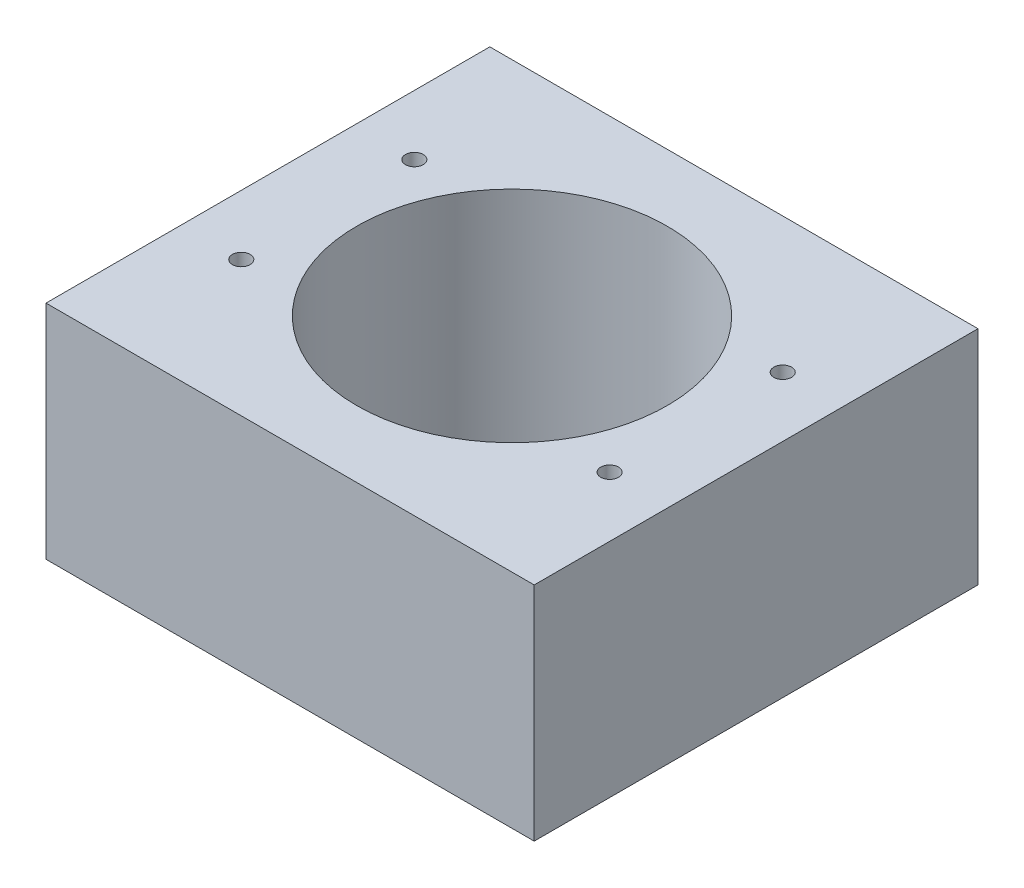
SolidWorks part; units mm, degrees
ref_plane "Front Plane" through (0, 0, 0) normal (0, 0, 1) x (1, 0, 0)
ref_plane "Top Plane" through (0, 0, 0) normal (0, 1, 0) x (1, 0, 0)
ref_plane "Right Plane" through (0, 0, 0) normal (1, 0, 0) x (0, 0, -1)
sketch "Sketch1" plane through (0, 0, 0) normal (0, 1, 0) x (1, 0, 0)
  line L1 (-55, 50) -> (55, 50)
  line L2 (-55, 50) -> (-55, -50)
  line L3 (-55, -50) -> (55, -50)
  line L4 (55, 50) -> (55, -50)
  line L5 (-55, 50) -> (55, -50) construction
  line L6 (-55, -50) -> (55, 50) construction
  point P0 (0, 0)
extrude "Boss-Extrude1" add sketch "Sketch1" along normal blind 50
sketch "Sketch2" plane through (0, 0, 0) normal (0, 1, 0) x (1, 0, 0)
  circle A0 centre (0, 0) radius 35
extrude "Cut-Extrude1" cut sketch "Sketch2" along normal blind 50
sketch "Sketch3" plane through (0, 0, 0) normal (0, 1, 0) x (1, 0, 0)
  line L0 (-55, -50) -> (55, -50) construction
  line L1 (55, -50) -> (55, 50) construction
  circle A0 centre (41.5, -19.5) radius 2
  dimension "D1" = 4
  dimension "D2" = 13.5
  dimension "29.5" = 30.5
extrude "Cut-Extrude2" cut sketch "Sketch3" along normal blind 50
mirror "Mirror1" about plane through (0, 0, 0) normal (0, 0, 1) of "Cut-Extrude2"
mirror "Mirror2" about plane through (0, 0, 0) normal (1, 0, 0) of "Cut-Extrude2"
mirror "Mirror3" about plane through (0, 0, 0) normal (0, 0, 1) of "Mirror2"
